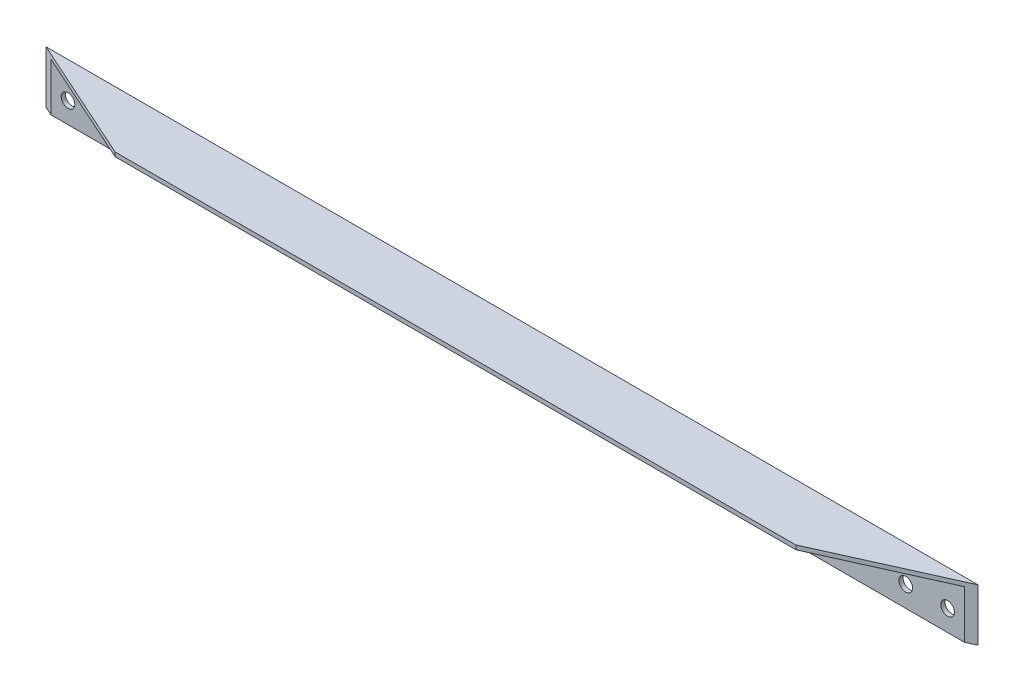
SolidWorks part; units mm, degrees
ref_plane "前视" through (0, 0, 0) normal (0, 0, 1) x (1, 0, 0)
ref_plane "上视" through (0, 0, 0) normal (0, 1, 0) x (1, 0, 0)
ref_plane "右视" through (0, 0, 0) normal (1, 0, 0) x (0, 0, -1)
sketch "草图1" plane through (0, 0, 0) normal (0, 0, 1) x (1, 0, 0)
  line L0 (0, 0) -> (0, 72.6209) construction
  line L1 (-890, 0) -> (890, 0)
  line L2 (-890, 0) -> (-890, 100)
  line L3 (-890, 100) -> (890, 100)
  line L4 (890, 0) -> (890, 100)
  line L5 (1568.3745, 40) -> (1028.9756, 40) construction
  line L6 (1022.2249, 40) -> (468.717, 40) construction
  line L7 (468.717, 40) -> (338.4799, 40) construction
  line L8 (346.077, 40) -> (224.5223, 40) construction
  line L9 (0, 72.6209) -> (0, 232.7989) construction
  line L10 (1000, 433.3131) -> (1000, -1026.6948) construction
  line L11 (-1000, 516.3236) -> (-1000, -1344.0878) construction
  circle A0 centre (840, 40) radius 13
  circle A1 centre (760, 40) radius 13
  circle A7 centre (-840, 40) radius 13
  circle A8 centre (-760, 40) radius 13
  dimension "D4" = 26
  dimension "D5" = 26
  dimension "D8" = 160
  dimension "D1" = 1780
  dimension "D2" = 100
  dimension "D3" = 40
  dimension "D6" = 50
  dimension "D7" = 80
  dimension "D9" = 160
extrude "基体-拉伸" add sketch "草图1" along normal blind 8
sketch "草图2" plane through (0, 0, 8) normal (0, 0, 1) x (1, 0, 0)
  line L0 (890, 0) -> (890, 100) construction
  line L1 (-890, 100) -> (890, 100)
  line L2 (-890, 100) -> (-890, 92)
  line L3 (-890, 92) -> (890, 92)
  line L4 (890, 100) -> (890, 92)
  dimension "D1" = 8
extrude "凸台-拉伸1" add sketch "草图2" along normal blind 100
sketch "草图3" plane through (0, 100, 0) normal (0, 1, 0) x (-1, 0, 0)
  line L0 (-890, 108) -> (890, 108) construction
  line L1 (-650, 108) -> (-890, 0)
  line L2 (-890, 0) -> (-890, 108)
  line L3 (-890, 108) -> (-650, 108)
  line L4 (0, -34.4051) -> (0, 171.3565) construction
  line L5 (890, 108) -> (650, 108)
  line L6 (890, 0) -> (890, 108)
  line L7 (650, 108) -> (890, 0)
  point P0 (-650, 108)
  dimension "D1" = 240
extrude "切除-拉伸1" cut sketch "草图3" against normal through all
